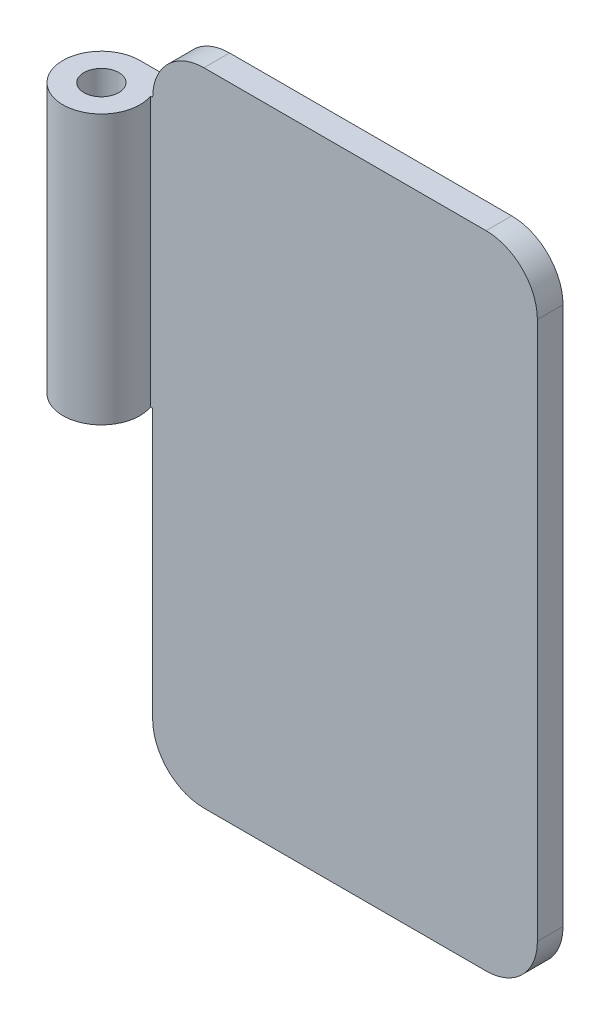
SolidWorks part; units mm, degrees
ref_plane "前视基准面" through (0, 0, 0) normal (0, 0, 1) x (1, 0, 0)
ref_plane "上视基准面" through (0, 0, 0) normal (0, 1, 0) x (1, 0, 0)
ref_plane "右视基准面" through (0, 0, 0) normal (1, 0, 0) x (0, 0, -1)
other "Configuration Table"
sketch "草图1" plane through (0, 0, 0) normal (0, 0, 1) x (1, 0, 0)
  line L1 (17.75, -8.875) -> (6.75, -8.875)
  line L2 (19.75, -6.875) -> (19.75, 14.125)
  line L3 (17.75, 16.125) -> (6.75, 16.125)
  line L4 (4.75, -6.875) -> (4.75, 14.125)
  line L5 (19.75, -8.875) -> (4.75, 16.125) construction
  line L6 (19.75, 16.125) -> (4.75, -8.875) construction
  arc A0 (6.75, 16.125) -> (4.75, 14.125) centre (6.75, 14.125) ccw
  arc A1 (4.75, -6.875) -> (6.75, -8.875) centre (6.75, -6.875) ccw
  arc A2 (17.75, -8.875) -> (19.75, -6.875) centre (17.75, -6.875) ccw
  arc A3 (19.75, 14.125) -> (17.75, 16.125) centre (17.75, 14.125) ccw
  point P0 (12.25, 3.625)
  dimension "D3" = 2
  dimension "D1" = 15
  dimension "D2" = 25
extrude "凸台-拉伸1" add sketch "草图1" along normal blind 1
ref_plane "基准面2" through (0, 0, 1.5) normal (0, 0, 1) x (1, 0, 0)
sketch "草图9" plane through (0, 0, 1.5) normal (0, 0, 1) x (1, 0, 0)
  line L1 (3.93, 14.125) -> (3.93, 3.625)
  line L2 (4.75, 14.125) -> (3.25, 14.125)
  line L3 (4.75, 14.125) -> (4.75, 3.625)
  line L4 (4.75, 3.625) -> (3.25, 3.625)
  line L5 (3.25, 14.125) -> (3.25, 3.625)
  line L6 (4.75, 14.125) -> (3.25, 3.625) construction
  line L7 (4.75, 3.625) -> (3.25, 14.125) construction
  line L8 (4.75, 14.125) -> (4.75, -6.875) construction
  line L9 (4.75, 14.125) -> (4.75, -6.875)
  line L10 (17.75, 16.125) -> (6.75, 16.125) construction
  point P2 (4, 8.875)
  dimension "D1" = 10.5
  dimension "D2" = 1.5
  dimension "D3" = 0.68
  dimension "D4" = 12.5
revolve "旋转2" add sketch "草图9" angle 360 about L5
sketch "草图11" plane through (0, 14.125, 0) normal (0, 1, 0) x (1, 0, 0)
  line L1 (4.75, 0) -> (3.25, 0)
  line L2 (4.75, 0) -> (4.75, -0.82)
  line L3 (4.75, -0.82) -> (3.25, -0.82)
  line L4 (3.25, 0) -> (3.25, -0.82)
  line L5 (4.75, -1) -> (4.4252, -1)
  line L6 (4.75, -1) -> (4.75, -0.82)
  line L7 (4.75, -0.82) -> (4.4252, -0.82)
  line L8 (4.4252, -1) -> (4.4252, -0.82)
  circle A0 centre (3.25, -1.5) radius 0.68 construction
  circle A1 centre (3.25, -1.5) radius 1.5 construction
  circle A2 centre (3.25, -1.5) radius 1.5
  circle M6 centre (3.25, -1.5) radius 1.5
extrude "凸台-拉伸4" add sketch "草图11" against normal up to surface (10.5 mm away) contours L5 L6 L3 M6 | L3 L2 L1 M6 up to face at (2.57, 3.625, 1.5)
